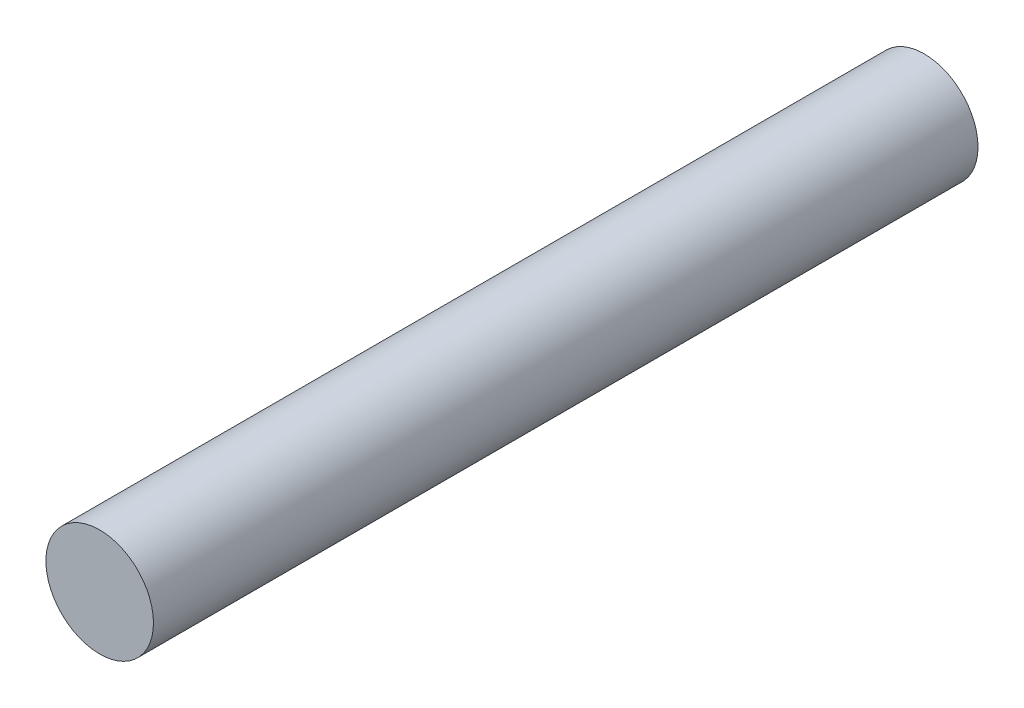
SolidWorks part; units mm, degrees
ref_plane "정면" through (0, 0, 0) normal (0, 0, 1) x (1, 0, 0)
ref_plane "윗면" through (0, 0, 0) normal (0, 1, 0) x (1, 0, 0)
ref_plane "우측면" through (0, 0, 0) normal (1, 0, 0) x (0, 0, -1)
sketch "스케치1" plane through (0, 0, 0) normal (0, 0, 1) x (1, 0, 0)
  circle A0 centre (0, 0) radius 3
  dimension "D1" = 6
extrude "보스-돌출1" add sketch "스케치1" along normal blind 46
